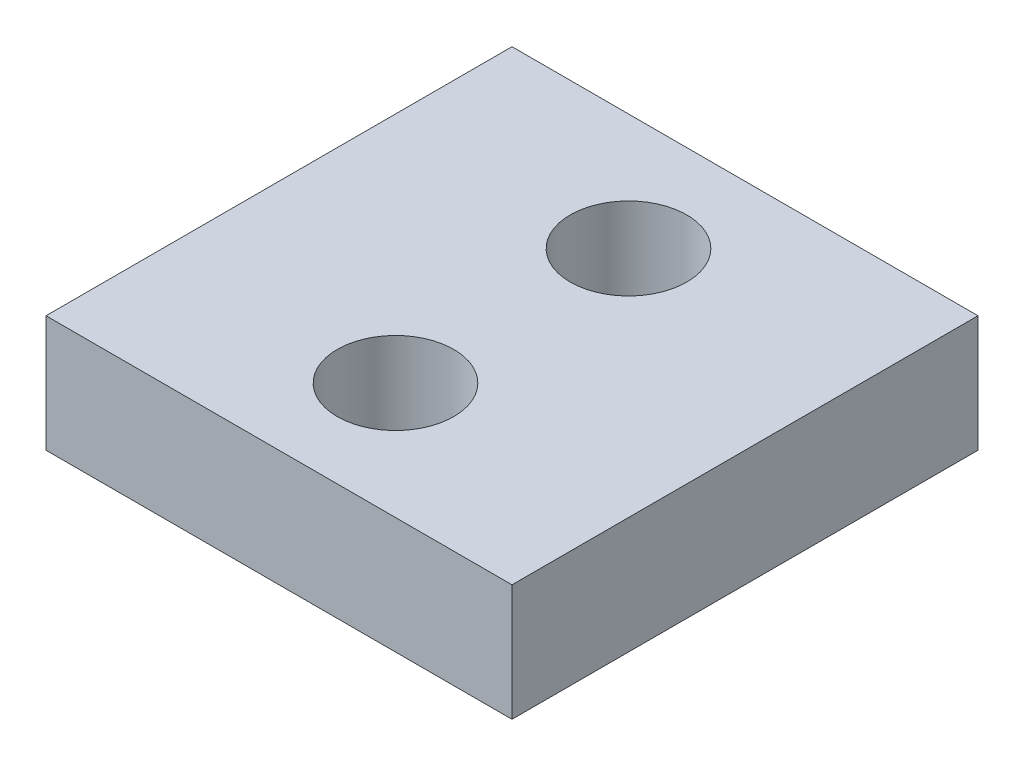
SolidWorks part; units mm, degrees
material "6061 Alloy"
ref_plane "Front Plane" through (0, 0, 0) normal (0, 0, 1) x (1, 0, 0)
ref_plane "Top Plane" through (0, 0, 0) normal (0, 1, 0) x (1, 0, 0)
ref_plane "Right Plane" through (0, 0, 0) normal (1, 0, 0) x (0, 0, -1)
sketch "Sketch1" plane through (0, 0, 0) normal (0, 1, 0) x (1, 0, 0)
  line L1 (12.7, -12.7) -> (-12.7, -12.7)
  line L2 (12.7, -12.7) -> (12.7, 12.7)
  line L3 (12.7, 12.7) -> (-12.7, 12.7)
  line L4 (-12.7, -12.7) -> (-12.7, 12.7)
  line L5 (12.7, -12.7) -> (-12.7, 12.7) construction
  line L6 (12.7, 12.7) -> (-12.7, -12.7) construction
  point P0 (0, 0)
  dimension "D1" = 25.4
  dimension "D2" = 25.4
extrude "Boss-Extrude1" add sketch "Sketch1" along normal blind 6.35
hole_wizard "1/4 (0.25) Diameter Hole1" positions "Sketch3" profile "Sketch2" hole size "1/4" standard "Ansi Inch" end condition through all
sketch "Sketch3" plane through (0, 6.35, 0) normal (0, 1, 0) x (-1, 0, 0)
  line L0 (0, 12.7) -> (0, -12.7) construction
  line L1 (12.7, 12.7) -> (-12.7, 12.7) construction
  line L2 (-12.7, -12.7) -> (12.7, -12.7) construction
  line L4 (0, 0) -> (7.5342, 0) construction
  point P0 (0, 6.35)
  point P1 (0, -6.35)
  dimension "D1" = 6.35
sketch "Sketch2" plane through (0, 6.35, 6.35) normal (1, 0, 0) x (0, 0, 1)
  line L0 (0, 0) -> (0, 6.35)
  line L1 (0, 6.35) -> (3.175, 6.35)
  line L2 (3.175, 6.35) -> (3.175, 0)
  line L5 (3.175, 0) -> (0, 0)
  line L11 (0, -6.35) -> (0, 107.95) construction
  dimension "Thru Hole Dia." = 6.35
  dimension "Thru Hole Depth" = 6.35
